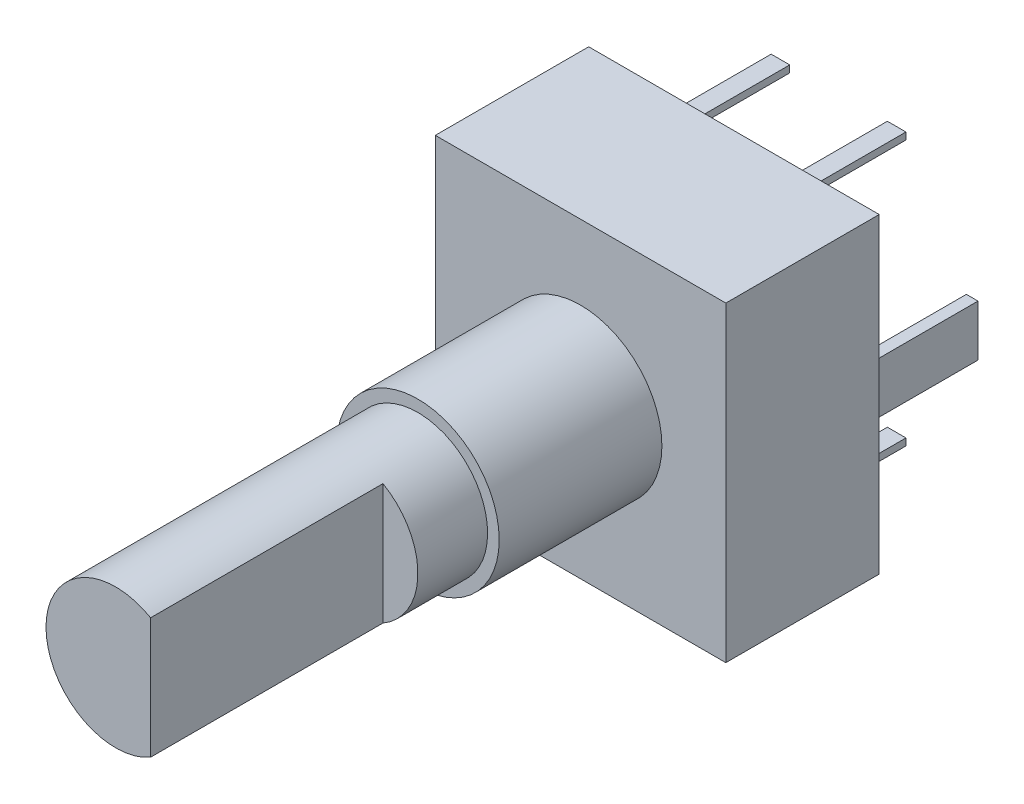
SolidWorks part; units mm, degrees
ref_plane "Front Plane" through (0, 0, 0) normal (0, 0, 1) x (1, 0, 0)
ref_plane "Top Plane" through (0, 0, 0) normal (0, 1, 0) x (1, 0, 0)
ref_plane "Right Plane" through (0, 0, 0) normal (1, 0, 0) x (0, 0, -1)
sketch "Sketch1" plane through (0, 0, 0) normal (0, 0, 1) x (1, 0, 0)
  line L1 (-6.25, -6.7) -> (6.25, -6.7)
  line L2 (-6.25, -6.7) -> (-6.25, 6.7)
  line L3 (-6.25, 6.7) -> (6.25, 6.7)
  line L4 (6.25, -6.7) -> (6.25, 6.7)
extrude "Body" add sketch "Sketch1" along normal blind 6.6
ref_plane "Plane_z6_6" through (0, 0, 6.6) normal (0, 0, 1) x (1, 0, 0)
sketch "Sketch2" plane through (0, 0, 6.6) normal (0, 0, 1) x (1, 0, 0)
  circle A0 centre (0, 0) radius 3.5
extrude "Bushing" add sketch "Sketch2" along normal blind 7
ref_plane "Plane_z13_6" through (0, 0, 13.6) normal (0, 0, 1) x (1, 0, 0)
sketch "Sketch3" plane through (0, 0, 13.6) normal (0, 0, 1) x (1, 0, 0)
  circle A0 centre (0, 0) radius 3
extrude "Shaft" add sketch "Sketch3" along normal blind 13
sketch "Sketch4" plane through (0, 0, 0) normal (0, 0, 1) x (1, 0, 0)
  line L1 (-2.9, -5.85) -> (-2.1, -5.85)
  line L2 (-2.9, -5.85) -> (-2.9, -5.55)
  line L3 (-2.9, -5.55) -> (-2.1, -5.55)
  line L4 (-2.1, -5.85) -> (-2.1, -5.55)
  line L6 (-0.4, -5.85) -> (0.4, -5.85)
  line L7 (-0.4, -5.85) -> (-0.4, -5.55)
  line L8 (-0.4, -5.55) -> (0.4, -5.55)
  line L9 (0.4, -5.85) -> (0.4, -5.55)
  line L11 (2.1, -5.85) -> (2.9, -5.85)
  line L12 (2.1, -5.85) -> (2.1, -5.55)
  line L13 (2.1, -5.55) -> (2.9, -5.55)
  line L14 (2.9, -5.85) -> (2.9, -5.55)
  line L16 (-2.9, 5.55) -> (-2.1, 5.55)
  line L17 (-2.9, 5.55) -> (-2.9, 5.85)
  line L18 (-2.9, 5.85) -> (-2.1, 5.85)
  line L19 (-2.1, 5.55) -> (-2.1, 5.85)
  line L21 (2.1, 5.55) -> (2.9, 5.55)
  line L22 (2.1, 5.55) -> (2.1, 5.85)
  line L23 (2.1, 5.85) -> (2.9, 5.85)
  line L24 (2.9, 5.55) -> (2.9, 5.85)
extrude "Pins" add sketch "Sketch4" against normal blind 4.5
sketch "Sketch5" plane through (0, 0, 0) normal (0, 0, 1) x (1, 0, 0)
  line L1 (-6, -1.1) -> (-5.5, -1.1)
  line L2 (-6, -1.1) -> (-6, 1.1)
  line L3 (-6, 1.1) -> (-5.5, 1.1)
  line L4 (-5.5, -1.1) -> (-5.5, 1.1)
  line L6 (5.5, -1.1) -> (6, -1.1)
  line L7 (5.5, -1.1) -> (5.5, 1.1)
  line L8 (5.5, 1.1) -> (6, 1.1)
  line L9 (6, -1.1) -> (6, 1.1)
extrude "Tabs" add sketch "Sketch5" against normal blind 4.5
ref_plane "Plane_z26_6" through (0, 0, 26.6) normal (0, 0, 1) x (1, 0, 0)
sketch "Sketch6" plane through (0, 0, 26.6) normal (0, 0, 1) x (1, 0, 0)
  line L1 (1.5, -4) -> (5.5, -4)
  line L2 (1.5, -4) -> (1.5, 4)
  line L3 (1.5, 4) -> (5.5, 4)
  line L4 (5.5, -4) -> (5.5, 4)
extrude "D_flat" cut sketch "Sketch6" against normal blind 10
